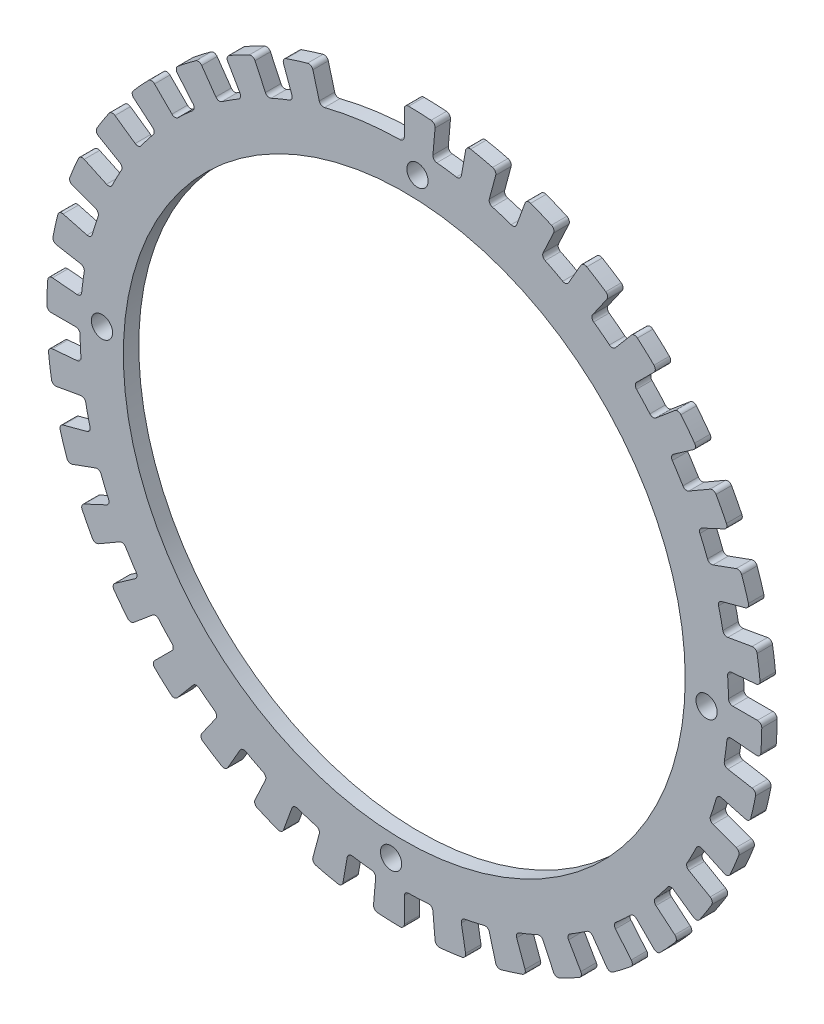
SolidWorks part; units mm, degrees
ref_plane "Front Plane" through (0, 0, 0) normal (0, 0, 1) x (1, 0, 0)
ref_plane "Top Plane" through (0, 0, 0) normal (0, 1, 0) x (1, 0, 0)
ref_plane "Right Plane" through (0, 0, 0) normal (1, 0, 0) x (0, 0, -1)
sketch "Sketch1" plane through (0, 0, 0) normal (0, 0, 1) x (1, 0, 0)
  line L0 (0, 82.7) -> (0, 75) construction
  line L1 (7.2078, 82.3853) -> (6.5367, 74.7146) construction
  line L2 (0, 75) -> (0, 0) construction
  line L3 (6.5367, 74.7146) -> (0, 0) construction
  line L4 (13.1961, 74.8389) -> (14.186, 80.4528) construction
  line L5 (13.1961, 74.8389) -> (0, 0) construction
  line L8 (0, 0) -> (3.0531, 69.9286) construction
  line L12 (3.2715, 74.9286) -> (3.0531, 69.9286) construction
  line L15 (3.0531, 69.9286) -> (2.8348, 64.9286) construction
  line L18 (7.6195, 75.6171) -> (6.6233, 75.7042) construction
  line L21 (7.6195, 75.6171) -> (7.5192, 74.6221) construction
  line L24 (13.1961, 74.8389) -> (12.2113, 75.0126) construction
  line L27 (12.2113, 75.0126) -> (12.0506, 74.0256) construction
  line L30 (1.0122, 82.6938) -> (1, 81.6939) construction
  line L33 (1, 81.6939) -> (0, 81.6939) construction
  line L36 (7.1201, 81.383) -> (6.1239, 81.4702) construction
  line L39 (6.1239, 81.4702) -> (6.1989, 82.4674) construction
  line L42 (7.1201, 81.383) -> (6.6233, 75.7042)
  line L45 (0, 81.6939) -> (0, 75.9934)
  line L48 (0, 75.9934) -> (-1, 75.9934) construction
  line L51 (-1, 75.9934) -> (-0.9868, 74.9935) construction
  line L54 (14.186, 80.4528) -> (13.1961, 74.8389)
  line L57 (21.1439, 78.9102) -> (19.6685, 73.404)
  line L59 (27.941, 76.7671) -> (25.9913, 71.4105)
  line L62 (34.5253, 74.0398) -> (32.1162, 68.8734)
  line L65 (40.8469, 70.749) -> (37.9967, 65.8122)
  line L68 (46.8577, 66.9197) -> (43.588, 62.2502)
  line L72 (52.5118, 62.5811) -> (48.8476, 58.2143)
  line L74 (57.7663, 57.7663) -> (53.7355, 53.7355)
  line L77 (62.5811, 52.5118) -> (58.2143, 48.8476)
  line L80 (66.9197, 46.8577) -> (62.2502, 43.588)
  line L83 (70.749, 40.8469) -> (65.8122, 37.9967)
  line L86 (74.0398, 34.5253) -> (68.8734, 32.1162)
  line L89 (76.7671, 27.941) -> (71.4105, 25.9913)
  line L92 (78.9102, 21.1439) -> (73.404, 19.6685)
  line L95 (80.4528, 14.186) -> (74.8389, 13.1961)
  line L98 (81.383, 7.1201) -> (75.7042, 6.6233)
  line L101 (81.6939, 0) -> (75.9934, 0)
  line L104 (81.383, -7.1201) -> (75.7042, -6.6233)
  line L107 (80.4528, -14.186) -> (74.8389, -13.1961)
  line L108 (78.9102, -21.1439) -> (73.404, -19.6685)
  line L109 (0, -82.7) -> (0, -75) [skipped]
  line L110 (76.7671, -27.941) -> (71.4105, -25.9913)
  line L111 (14.3607, 81.4436) -> (13.0236, 73.8606) [skipped]
  line L112 (74.0398, -34.5253) -> (68.8734, -32.1162)
  line L113 (70.749, -40.8469) -> (65.8122, -37.9967)
  line L114 (66.9197, -46.8577) -> (62.2502, -43.588)
  line L115 (41.35, 71.6203) -> (37.5, 64.9519) [skipped]
  line L116 (62.5811, -52.5118) -> (58.2143, -48.8476)
  line L117 (53.1585, 63.3519) -> (48.2091, 57.4533) [skipped]
  line L118 (-63.3519, -53.1585) -> (-57.4533, -48.2091) [skipped]
  line L119 (63.3519, 53.1585) -> (57.4533, 48.2091) [skipped]
  line L120 (57.7663, -57.7663) -> (53.7355, -53.7355)
  line L121 (71.6203, 41.35) -> (64.9519, 37.5) [skipped]
  line L122 (52.5118, -62.5811) -> (48.8476, -58.2143)
  line L123 (77.7126, 28.2851) -> (70.4769, 25.6515) [skipped]
  line L124 (46.8577, -66.9197) -> (43.588, -62.2502)
  line L125 (81.4436, 14.3607) -> (73.8606, 13.0236) [skipped]
  line L126 (40.8469, -70.749) -> (37.9967, -65.8122)
  line L127 (82.7, 0) -> (75, 0) [skipped]
  line L128 (34.5253, -74.0398) -> (32.1162, -68.8734)
  line L129 (81.4436, -14.3607) -> (73.8606, -13.0236) [skipped]
  line L130 (27.941, -76.7671) -> (25.9913, -71.4105)
  line L131 (77.7126, -28.2851) -> (70.4769, -25.6515) [skipped]
  line L132 (21.1439, -78.9102) -> (19.6685, -73.404)
  line L133 (71.6203, -41.35) -> (64.9519, -37.5) [skipped]
  line L134 (14.186, -80.4528) -> (13.1961, -74.8389)
  line L135 (63.3519, -53.1585) -> (57.4533, -48.2091) [skipped]
  line L136 (7.1201, -81.383) -> (6.6233, -75.7042)
  line L137 (53.1585, -63.3519) -> (48.2091, -57.4533) [skipped]
  line L138 (0, -81.6939) -> (0, -75.9934)
  line L139 (41.35, -71.6203) -> (37.5, -64.9519) [skipped]
  line L140 (-7.1201, -81.383) -> (-6.6233, -75.7042)
  line L141 (28.2851, -77.7126) -> (25.6515, -70.4769) [skipped]
  line L142 (14.3607, -81.4436) -> (13.0236, -73.8606) [skipped]
  line L143 (34.9505, 74.9517) -> (31.6964, 67.9731) [skipped]
  line L144 (47.4348, 67.7439) -> (43.0182, 61.4364) [skipped]
  line L145 (58.4777, 58.4777) -> (53.033, 53.033) [skipped]
  line L146 (67.7439, 47.4348) -> (61.4364, 43.0182) [skipped]
  line L147 (74.9517, 34.9505) -> (67.9731, 31.6964) [skipped]
  line L148 (79.8821, 21.4043) -> (72.4444, 19.4114) [skipped]
  line L149 (82.3853, 7.2078) -> (74.7146, 6.5367) [skipped]
  line L150 (82.3853, -7.2078) -> (74.7146, -6.5367) [skipped]
  line L151 (79.8821, -21.4043) -> (72.4444, -19.4114) [skipped]
  line L152 (74.9517, -34.9505) -> (67.9731, -31.6964) [skipped]
  line L153 (67.7439, -47.4348) -> (61.4364, -43.0182) [skipped]
  line L154 (58.4777, -58.4777) -> (53.033, -53.033) [skipped]
  line L155 (47.4348, -67.7439) -> (43.0182, -61.4364) [skipped]
  line L156 (34.9505, -74.9517) -> (31.6964, -67.9731) [skipped]
  line L157 (21.4043, -79.8821) -> (19.4114, -72.4444) [skipped]
  line L158 (7.2078, -82.3853) -> (6.5367, -74.7146) [skipped]
  line L159 (-7.2078, -82.3853) -> (-6.5367, -74.7146) [skipped]
  line L160 (-21.4043, -79.8821) -> (-19.4114, -72.4444) [skipped]
  line L161 (-34.9505, -74.9517) -> (-31.6964, -67.9731) [skipped]
  line L162 (-47.4348, -67.7439) -> (-43.0182, -61.4364) [skipped]
  line L163 (-58.4777, -58.4777) -> (-53.033, -53.033) [skipped]
  line L164 (-67.7439, -47.4348) -> (-61.4364, -43.0182) [skipped]
  line L165 (-74.9517, -34.9505) -> (-67.9731, -31.6964) [skipped]
  line L166 (-79.8821, -21.4043) -> (-72.4444, -19.4114) [skipped]
  line L167 (-82.3853, -7.2078) -> (-74.7146, -6.5367) [skipped]
  line L168 (-82.3853, 7.2078) -> (-74.7146, 6.5367) [skipped]
  line L169 (-79.8821, 21.4043) -> (-72.4444, 19.4114) [skipped]
  line L170 (-74.9517, 34.9505) -> (-67.9731, 31.6964) [skipped]
  line L171 (-67.7439, 47.4348) -> (-61.4364, 43.0182) [skipped]
  line L172 (-58.4777, 58.4777) -> (-53.033, 53.033) [skipped]
  line L173 (-47.4348, 67.7439) -> (-43.0182, 61.4364) [skipped]
  line L174 (-34.9505, 74.9517) -> (-31.6964, 67.9731) [skipped]
  line L175 (-21.4043, 79.8821) -> (-19.4114, 72.4444) [skipped]
  line L176 (21.4043, 79.8821) -> (19.4114, 72.4444) [skipped]
  line L177 (-14.186, -80.4528) -> (-13.1961, -74.8389)
  line L178 (-21.1439, -78.9102) -> (-19.6685, -73.404)
  line L179 (-27.941, -76.7671) -> (-25.9913, -71.4105)
  line L180 (-34.5253, -74.0398) -> (-32.1162, -68.8734)
  line L181 (-40.8469, -70.749) -> (-37.9967, -65.8122)
  line L182 (-46.8577, -66.9197) -> (-43.588, -62.2502)
  line L183 (-52.5118, -62.5811) -> (-48.8476, -58.2143)
  line L184 (-57.7663, -57.7663) -> (-53.7355, -53.7355)
  line L185 (-62.5811, -52.5118) -> (-58.2143, -48.8476)
  line L186 (-66.9197, -46.8577) -> (-62.2502, -43.588)
  line L187 (-70.749, -40.8469) -> (-65.8122, -37.9967)
  line L188 (-74.0398, -34.5253) -> (-68.8734, -32.1162)
  line L189 (-76.7671, -27.941) -> (-71.4105, -25.9913)
  line L190 (-78.9102, -21.1439) -> (-73.404, -19.6685)
  line L191 (-80.4528, -14.186) -> (-74.8389, -13.1961)
  line L192 (-81.383, -7.1201) -> (-75.7042, -6.6233)
  line L193 (-81.6939, 0) -> (-75.9934, 0)
  line L194 (-81.383, 7.1201) -> (-75.7042, 6.6233)
  line L195 (-80.4528, 14.186) -> (-74.8389, 13.1961)
  line L196 (-78.9102, 21.1439) -> (-73.404, 19.6685)
  line L197 (-76.7671, 27.941) -> (-71.4105, 25.9913)
  line L198 (-74.0398, 34.5253) -> (-68.8734, 32.1162)
  line L199 (-70.749, 40.8469) -> (-65.8122, 37.9967)
  line L200 (-66.9197, 46.8577) -> (-62.2502, 43.588)
  line L201 (-62.5811, 52.5118) -> (-58.2143, 48.8476)
  line L202 (-57.7663, 57.7663) -> (-53.7355, 53.7355)
  line L203 (-52.5118, 62.5811) -> (-48.8476, 58.2143)
  line L204 (-46.8577, 66.9197) -> (-43.588, 62.2502)
  line L205 (-40.8469, 70.749) -> (-37.9967, 65.8122)
  line L206 (-34.5253, 74.0398) -> (-32.1162, 68.8734)
  line L207 (-27.941, 76.7671) -> (-25.9913, 71.4105)
  line L208 (-21.1439, 78.9102) -> (-19.6685, 73.404)
  circle A0 centre (0, 0) radius 82.7 construction
  circle A1 centre (0, 0) radius 64.9905
  circle A73 centre (3.0531, 69.9286) radius 2.4585
  circle A74 centre (3.0531, 69.9286) radius 2.987 construction
  arc A78 (0, 75) -> (6.5367, 74.7146) centre (0, 0) cw construction
  arc A79 (6.6233, 75.7042) -> (7.5192, 74.6221) centre (7.6195, 75.6171) ccw
  arc A80 (12.0506, 74.0256) -> (13.1961, 74.8389) centre (12.2113, 75.0126) ccw construction
  arc A81 (7.1201, 81.383) -> (6.1989, 82.4674) centre (6.1239, 81.4702) ccw
  arc A82 (0, 81.6939) -> (1.0122, 82.6938) centre (1, 81.6939) cw
  arc A83 (6.5367, 74.7146) -> (13.0236, 73.8606) centre (0, 0) cw [skipped]
  arc A84 (7.5192, 74.6221) -> (12.0506, 74.0256) centre (0, 0) cw
  arc A85 (0, 82.7) -> (7.2078, 82.3853) centre (0, 0) cw [skipped]
  arc A86 (1.0122, 82.6938) -> (6.1989, 82.4674) centre (0, 0) cw
  arc A87 (28.2851, 77.7126) -> (34.9505, 74.9517) centre (0, 0) cw [skipped]
  arc A88 (31.6964, 67.9731) -> (37.5, 64.9519) centre (0, 0) cw [skipped]
  arc A89 (41.35, 71.6203) -> (47.4348, 67.7439) centre (0, 0) cw [skipped]
  arc A90 (43.0182, 61.4364) -> (48.2091, 57.4533) centre (0, 0) cw [skipped]
  arc A91 (53.1585, 63.3519) -> (58.4777, 58.4777) centre (0, 0) cw [skipped]
  arc A92 (53.033, 53.033) -> (57.4533, 48.2091) centre (0, 0) cw [skipped]
  arc A93 (63.3519, 53.1585) -> (67.7439, 47.4348) centre (0, 0) cw [skipped]
  arc A94 (61.4364, 43.0182) -> (64.9519, 37.5) centre (0, 0) cw [skipped]
  arc A95 (71.6203, 41.35) -> (74.9517, 34.9505) centre (0, 0) cw [skipped]
  arc A96 (67.9731, 31.6964) -> (70.4769, 25.6515) centre (0, 0) cw [skipped]
  arc A97 (77.7126, 28.2851) -> (79.8821, 21.4043) centre (0, 0) cw [skipped]
  arc A98 (72.4444, 19.4114) -> (73.8606, 13.0236) centre (0, 0) cw [skipped]
  arc A99 (81.4436, 14.3607) -> (82.3853, 7.2078) centre (0, 0) cw [skipped]
  arc A100 (74.7146, 6.5367) -> (75, 0) centre (0, 0) cw [skipped]
  arc A101 (82.7, 0) -> (82.3853, -7.2078) centre (0, 0) cw [skipped]
  arc A102 (74.7146, -6.5367) -> (73.8606, -13.0236) centre (0, 0) cw [skipped]
  arc A103 (81.4436, -14.3607) -> (79.8821, -21.4043) centre (0, 0) cw [skipped]
  arc A104 (72.4444, -19.4114) -> (70.4769, -25.6515) centre (0, 0) cw [skipped]
  arc A105 (77.7126, -28.2851) -> (74.9517, -34.9505) centre (0, 0) cw [skipped]
  arc A106 (67.9731, -31.6964) -> (64.9519, -37.5) centre (0, 0) cw [skipped]
  arc A107 (71.6203, -41.35) -> (67.7439, -47.4348) centre (0, 0) cw [skipped]
  arc A108 (61.4364, -43.0182) -> (57.4533, -48.2091) centre (0, 0) cw [skipped]
  arc A109 (63.3519, -53.1585) -> (58.4777, -58.4777) centre (0, 0) cw [skipped]
  arc A110 (53.033, -53.033) -> (48.2091, -57.4533) centre (0, 0) cw [skipped]
  arc A111 (53.1585, -63.3519) -> (47.4348, -67.7439) centre (0, 0) cw [skipped]
  arc A112 (43.0182, -61.4364) -> (37.5, -64.9519) centre (0, 0) cw [skipped]
  arc A113 (41.35, -71.6203) -> (34.9505, -74.9517) centre (0, 0) cw [skipped]
  arc A114 (31.6964, -67.9731) -> (25.6515, -70.4769) centre (0, 0) cw [skipped]
  arc A115 (28.2851, -77.7126) -> (21.4043, -79.8821) centre (0, 0) cw [skipped]
  arc A116 (19.4114, -72.4444) -> (13.0236, -73.8606) centre (0, 0) cw [skipped]
  arc A117 (14.3607, -81.4436) -> (7.2078, -82.3853) centre (0, 0) cw [skipped]
  arc A118 (6.5367, -74.7146) -> (0, -75) centre (0, 0) cw [skipped]
  arc A119 (0, -82.7) -> (-7.2078, -82.3853) centre (0, 0) cw [skipped]
  arc A120 (-6.5367, -74.7146) -> (-13.0236, -73.8606) centre (0, 0) cw [skipped]
  arc A121 (-14.3607, -81.4436) -> (-21.4043, -79.8821) centre (0, 0) cw [skipped]
  arc A122 (-28.2851, -77.7126) -> (-34.9505, -74.9517) centre (0, 0) cw [skipped]
  arc A123 (-19.4114, -72.4444) -> (-25.6515, -70.4769) centre (0, 0) cw [skipped]
  arc A124 (-31.6964, -67.9731) -> (-37.5, -64.9519) centre (0, 0) cw [skipped]
  arc A125 (-41.35, -71.6203) -> (-47.4348, -67.7439) centre (0, 0) cw [skipped]
  arc A126 (-43.0182, -61.4364) -> (-48.2091, -57.4533) centre (0, 0) cw [skipped]
  arc A127 (-53.1585, -63.3519) -> (-58.4777, -58.4777) centre (0, 0) cw [skipped]
  arc A128 (-53.033, -53.033) -> (-57.4533, -48.2091) centre (0, 0) cw [skipped]
  arc A129 (-63.3519, -53.1585) -> (-67.7439, -47.4348) centre (0, 0) cw [skipped]
  arc A130 (-61.4364, -43.0182) -> (-64.9519, -37.5) centre (0, 0) cw [skipped]
  arc A131 (-71.6203, -41.35) -> (-74.9517, -34.9505) centre (0, 0) cw [skipped]
  arc A132 (-67.9731, -31.6964) -> (-70.4769, -25.6515) centre (0, 0) cw [skipped]
  arc A133 (-77.7126, -28.2851) -> (-79.8821, -21.4043) centre (0, 0) cw [skipped]
  arc A134 (-72.4444, -19.4114) -> (-73.8606, -13.0236) centre (0, 0) cw [skipped]
  arc A135 (-81.4436, -14.3607) -> (-82.3853, -7.2078) centre (0, 0) cw [skipped]
  arc A136 (-74.7146, -6.5367) -> (-75, 0) centre (0, 0) cw [skipped]
  arc A137 (-82.7, 0) -> (-82.3853, 7.2078) centre (0, 0) cw [skipped]
  arc A138 (-74.7146, 6.5367) -> (-73.8606, 13.0236) centre (0, 0) cw [skipped]
  arc A139 (-81.4436, 14.3607) -> (-79.8821, 21.4043) centre (0, 0) cw [skipped]
  arc A140 (-72.4444, 19.4114) -> (-70.4769, 25.6515) centre (0, 0) cw [skipped]
  arc A141 (-77.7126, 28.2851) -> (-74.9517, 34.9505) centre (0, 0) cw [skipped]
  arc A142 (-67.9731, 31.6964) -> (-64.9519, 37.5) centre (0, 0) cw [skipped]
  arc A143 (-71.6203, 41.35) -> (-67.7439, 47.4348) centre (0, 0) cw [skipped]
  arc A144 (-61.4364, 43.0182) -> (-57.4533, 48.2091) centre (0, 0) cw [skipped]
  arc A145 (-63.3519, 53.1585) -> (-58.4777, 58.4777) centre (0, 0) cw [skipped]
  arc A146 (-53.033, 53.033) -> (-48.2091, 57.4533) centre (0, 0) cw [skipped]
  arc A147 (-53.1585, 63.3519) -> (-47.4348, 67.7439) centre (0, 0) cw [skipped]
  arc A148 (-43.0182, 61.4364) -> (-37.5, 64.9519) centre (0, 0) cw [skipped]
  arc A149 (-41.35, 71.6203) -> (-34.9505, 74.9517) centre (0, 0) cw [skipped]
  arc A150 (-31.6964, 67.9731) -> (-25.6515, 70.4769) centre (0, 0) cw [skipped]
  arc A151 (-28.2851, 77.7126) -> (-21.4043, 79.8821) centre (0, 0) cw [skipped]
  arc A152 (-19.4114, 72.4444) -> (-13.0236, 73.8606) centre (0, 0) cw [skipped]
  arc A153 (14.3607, 81.4436) -> (21.4043, 79.8821) centre (0, 0) cw [skipped]
  arc A154 (19.4114, 72.4444) -> (25.6515, 70.4769) centre (0, 0) cw [skipped]
  arc A155 (0, 75.9934) -> (-0.9868, 74.9935) centre (-1, 75.9934) cw
  arc A156 (13.1961, 74.8389) -> (12.0506, 74.0256) centre (12.2113, 75.0126) cw
  arc A157 (14.186, 80.4528) -> (15.3565, 81.2617) centre (15.1708, 80.2791) cw
  arc A158 (15.3565, 81.2617) -> (20.425, 80.1381) centre (0, 0) cw
  arc A159 (21.1439, 78.9102) -> (20.425, 80.1381) centre (20.178, 79.169) ccw
  arc A160 (19.6685, 73.404) -> (20.363, 72.1828) centre (20.6345, 73.1452) ccw
  arc A161 (20.363, 72.1828) -> (24.722, 70.8084) centre (0, 0) cw
  arc A162 (25.9913, 71.4105) -> (24.722, 70.8084) centre (25.0516, 71.7525) cw
  arc A163 (27.941, 76.7671) -> (29.2341, 77.3606) centre (28.8806, 76.4251) cw
  arc A164 (29.2341, 77.3606) -> (34.0305, 75.3738) centre (0, 0) cw
  arc A165 (34.5253, 74.0398) -> (34.0305, 75.3738) centre (33.619, 74.4624) ccw
  arc A166 (32.1162, 68.8734) -> (32.588, 67.5501) centre (33.0225, 68.4508) ccw
  arc A167 (32.588, 67.5501) -> (36.6421, 65.4397) centre (0, 0) cw
  arc A168 (37.9967, 65.8122) -> (36.6421, 65.4397) centre (37.1307, 66.3122) cw
  arc A169 (40.8469, 70.749) -> (42.2235, 71.1088) centre (41.713, 70.249) cw
  arc A170 (42.2235, 71.1088) -> (46.602, 68.3194) centre (0, 0) cw
  arc A171 (46.8577, 66.9197) -> (46.602, 68.3194) centre (46.0385, 67.4933) ccw
  arc A172 (43.588, 62.2502) -> (43.8229, 60.8651) centre (44.4072, 61.6766) ccw
  arc A173 (43.8229, 60.8651) -> (47.4489, 58.0827) centre (0, 0) cw
  arc A174 (48.8476, 58.2143) -> (47.4489, 58.0827) centre (48.0816, 58.8571) cw
  arc A175 (52.5118, 62.5811) -> (53.93, 62.6965) centre (53.2779, 61.9384) cw
  arc A176 (53.93, 62.6965) -> (57.7576, 59.1891) centre (0, 0) cw
  arc A177 (57.7663, 57.7663) -> (57.7576, 59.1891) centre (57.0592, 58.4734) ccw
  arc A178 (53.7355, 53.7355) -> (53.7262, 52.3306) centre (54.4426, 53.0284) ccw
  arc A179 (53.7262, 52.3306) -> (56.814, 48.9609) centre (0, 0) cw
  arc A180 (58.2143, 48.8476) -> (56.814, 48.9609) centre (57.5716, 49.6137) cw
  arc A181 (62.5811, 52.5118) -> (63.9978, 52.3791) centre (63.2239, 51.7458) cw
  arc A182 (63.9978, 52.3791) -> (67.1582, 48.2604) centre (0, 0) cw
  arc A183 (66.9197, 46.8577) -> (67.1582, 48.2604) centre (66.3461, 47.6768) ccw
  arc A184 (62.2502, 43.588) -> (61.9971, 42.2061) centre (62.8237, 42.7689) ccw
  arc A185 (61.9971, 42.2061) -> (64.4529, 38.3514) centre (0, 0) cw
  arc A186 (65.8122, 37.9967) -> (64.4529, 38.3514) centre (65.3122, 38.8627) cw
  arc A187 (70.749, 40.8469) -> (72.1211, 40.4703) centre (71.249, 39.9809) cw
  arc A188 (72.1211, 40.4703) -> (74.5182, 35.8653) centre (0, 0) cw
  arc A189 (74.0398, 34.5253) -> (74.5182, 35.8653) centre (73.6172, 35.4316) ccw
  arc A190 (68.8734, 32.1162) -> (68.3843, 30.7992) centre (69.296, 31.2099) ccw
  arc A191 (68.3843, 30.7992) -> (70.1333, 26.5766) centre (0, 0) cw
  arc A192 (71.4105, 25.9913) -> (70.1333, 26.5766) centre (71.0684, 26.931) cw
  arc A193 (76.7671, 27.941) -> (78.053, 27.3318) centre (77.1092, 27.0013) cw
  arc A194 (78.053, 27.3318) -> (79.6141, 22.3805) centre (0, 0) cw
  arc A195 (78.9102, 21.1439) -> (79.6141, 22.3805) centre (78.6514, 22.1099) ccw
  arc A196 (73.404, 19.6685) -> (72.6936, 18.4565) centre (73.6628, 18.7026) ccw
  arc A197 (72.6936, 18.4565) -> (73.6828, 13.9943) centre (0, 0) cw
  arc A198 (74.8389, 13.1961) -> (73.6828, 13.9943) centre (74.6653, 14.1809) cw
  arc A199 (80.4528, 14.186) -> (81.6133, 13.3628) centre (80.6264, 13.2012) cw
  arc A200 (81.6133, 13.3628) -> (82.2909, 8.2156) centre (0, 0) cw
  arc A201 (81.383, 7.1201) -> (82.2909, 8.2156) centre (81.2959, 8.1163) ccw
  arc A202 (75.7042, 6.6233) -> (74.7941, 5.553) centre (75.7914, 5.6271) ccw
  arc A203 (74.7941, 5.553) -> (74.9935, 0.9868) centre (0, 0) cw
  arc A204 (75.9934, 0) -> (74.9935, 0.9868) centre (75.9934, 1) cw
  arc A205 (81.6939, 0) -> (82.6938, -1.0122) centre (81.6939, -1) cw
  arc A206 (82.6938, -1.0122) -> (82.4674, -6.1989) centre (0, 0) cw
  arc A207 (81.383, -7.1201) -> (82.4674, -6.1989) centre (81.4702, -6.1239) ccw
  arc A208 (75.7042, -6.6233) -> (74.6221, -7.5192) centre (75.6171, -7.6195) ccw
  arc A209 (74.6221, -7.5192) -> (74.0256, -12.0506) centre (0, 0) cw
  arc A210 (74.8389, -13.1961) -> (74.0256, -12.0506) centre (75.0126, -12.2113) cw
  arc A211 (80.4528, -14.186) -> (81.2617, -15.3565) centre (80.2791, -15.1708) cw
  arc A212 (81.2617, -15.3565) -> (80.1381, -20.425) centre (0, 0) cw
  arc A213 (78.9102, -21.1439) -> (80.1381, -20.425) centre (79.169, -20.178) ccw
  arc A214 (73.404, -19.6685) -> (72.1828, -20.363) centre (73.1452, -20.6345) ccw
  arc A215 (72.1828, -20.363) -> (70.8084, -24.722) centre (0, 0) cw
  arc A216 (71.4105, -25.9913) -> (70.8084, -24.722) centre (71.7525, -25.0516) cw
  arc A217 (76.7671, -27.941) -> (77.3606, -29.2341) centre (76.4251, -28.8806) cw
  arc A218 (77.3606, -29.2341) -> (75.3738, -34.0305) centre (0, 0) cw
  arc A219 (74.0398, -34.5253) -> (75.3738, -34.0305) centre (74.4624, -33.619) ccw
  arc A220 (68.8734, -32.1162) -> (67.5501, -32.588) centre (68.4508, -33.0225) ccw
  arc A221 (67.5501, -32.588) -> (65.4397, -36.6421) centre (0, 0) cw
  arc A222 (65.8122, -37.9967) -> (65.4397, -36.6421) centre (66.3122, -37.1307) cw
  arc A223 (70.749, -40.8469) -> (71.1088, -42.2235) centre (70.249, -41.713) cw
  arc A224 (71.1088, -42.2235) -> (68.3194, -46.602) centre (0, 0) cw
  arc A225 (66.9197, -46.8577) -> (68.3194, -46.602) centre (67.4933, -46.0385) ccw
  arc A226 (62.2502, -43.588) -> (60.8651, -43.8229) centre (61.6766, -44.4072) ccw
  arc A227 (60.8651, -43.8229) -> (58.0827, -47.4489) centre (0, 0) cw
  arc A228 (58.2143, -48.8476) -> (58.0827, -47.4489) centre (58.8571, -48.0816) cw
  arc A229 (62.5811, -52.5118) -> (62.6965, -53.93) centre (61.9384, -53.2779) cw
  arc A230 (62.6965, -53.93) -> (59.1891, -57.7576) centre (0, 0) cw
  arc A231 (57.7663, -57.7663) -> (59.1891, -57.7576) centre (58.4734, -57.0592) ccw
  arc A232 (53.7355, -53.7355) -> (52.3306, -53.7262) centre (53.0284, -54.4426) ccw
  arc A233 (52.3306, -53.7262) -> (48.9609, -56.814) centre (0, 0) cw
  arc A234 (48.8476, -58.2143) -> (48.9609, -56.814) centre (49.6137, -57.5716) cw
  arc A235 (52.5118, -62.5811) -> (52.3791, -63.9978) centre (51.7458, -63.2239) cw
  arc A236 (52.3791, -63.9978) -> (48.2604, -67.1582) centre (0, 0) cw
  arc A237 (46.8577, -66.9197) -> (48.2604, -67.1582) centre (47.6768, -66.3461) ccw
  arc A238 (43.588, -62.2502) -> (42.2061, -61.9971) centre (42.7689, -62.8237) ccw
  arc A239 (42.2061, -61.9971) -> (38.3514, -64.4529) centre (0, 0) cw
  arc A240 (37.9967, -65.8122) -> (38.3514, -64.4529) centre (38.8627, -65.3122) cw
  arc A241 (40.8469, -70.749) -> (40.4703, -72.1211) centre (39.9809, -71.249) cw
  arc A242 (40.4703, -72.1211) -> (35.8653, -74.5182) centre (0, 0) cw
  arc A243 (34.5253, -74.0398) -> (35.8653, -74.5182) centre (35.4316, -73.6172) ccw
  arc A244 (32.1162, -68.8734) -> (30.7992, -68.3843) centre (31.2099, -69.296) ccw
  arc A245 (30.7992, -68.3843) -> (26.5766, -70.1333) centre (0, 0) cw
  arc A246 (25.9913, -71.4105) -> (26.5766, -70.1333) centre (26.931, -71.0684) cw
  arc A247 (27.941, -76.7671) -> (27.3318, -78.053) centre (27.0013, -77.1092) cw
  arc A248 (27.3318, -78.053) -> (22.3805, -79.6141) centre (0, 0) cw
  arc A249 (21.1439, -78.9102) -> (22.3805, -79.6141) centre (22.1099, -78.6514) ccw
  arc A250 (19.6685, -73.404) -> (18.4565, -72.6936) centre (18.7026, -73.6628) ccw
  arc A251 (18.4565, -72.6936) -> (13.9943, -73.6828) centre (0, 0) cw
  arc A252 (13.1961, -74.8389) -> (13.9943, -73.6828) centre (14.1809, -74.6653) cw
  arc A253 (14.186, -80.4528) -> (13.3628, -81.6133) centre (13.2012, -80.6264) cw
  arc A254 (13.3628, -81.6133) -> (8.2156, -82.2909) centre (0, 0) cw
  arc A255 (7.1201, -81.383) -> (8.2156, -82.2909) centre (8.1163, -81.2959) ccw
  arc A256 (6.6233, -75.7042) -> (5.553, -74.7941) centre (5.6271, -75.7914) ccw
  arc A257 (5.553, -74.7941) -> (0.9868, -74.9935) centre (0, 0) cw
  arc A258 (0, -75.9934) -> (0.9868, -74.9935) centre (1, -75.9934) cw
  arc A259 (0, -81.6939) -> (-1.0122, -82.6938) centre (-1, -81.6939) cw
  arc A260 (-1.0122, -82.6938) -> (-6.1989, -82.4674) centre (0, 0) cw
  arc A261 (-7.1201, -81.383) -> (-6.1989, -82.4674) centre (-6.1239, -81.4702) ccw
  arc A262 (-6.6233, -75.7042) -> (-7.5192, -74.6221) centre (-7.6195, -75.6171) ccw
  arc A263 (-7.5192, -74.6221) -> (-12.0506, -74.0256) centre (0, 0) cw
  arc A264 (-13.1961, -74.8389) -> (-12.0506, -74.0256) centre (-12.2113, -75.0126) cw
  arc A265 (-14.186, -80.4528) -> (-15.3565, -81.2617) centre (-15.1708, -80.2791) cw
  arc A266 (-15.3565, -81.2617) -> (-20.425, -80.1381) centre (0, 0) cw
  arc A267 (-21.1439, -78.9102) -> (-20.425, -80.1381) centre (-20.178, -79.169) ccw
  arc A268 (-19.6685, -73.404) -> (-20.363, -72.1828) centre (-20.6345, -73.1452) ccw
  arc A269 (-20.363, -72.1828) -> (-24.722, -70.8084) centre (0, 0) cw
  arc A270 (-25.9913, -71.4105) -> (-24.722, -70.8084) centre (-25.0516, -71.7525) cw
  arc A271 (-27.941, -76.7671) -> (-29.2341, -77.3606) centre (-28.8806, -76.4251) cw
  arc A272 (-29.2341, -77.3606) -> (-34.0305, -75.3738) centre (0, 0) cw
  arc A273 (-34.5253, -74.0398) -> (-34.0305, -75.3738) centre (-33.619, -74.4624) ccw
  arc A274 (-32.1162, -68.8734) -> (-32.588, -67.5501) centre (-33.0225, -68.4508) ccw
  arc A275 (-32.588, -67.5501) -> (-36.6421, -65.4397) centre (0, 0) cw
  arc A276 (-37.9967, -65.8122) -> (-36.6421, -65.4397) centre (-37.1307, -66.3122) cw
  arc A277 (-40.8469, -70.749) -> (-42.2235, -71.1088) centre (-41.713, -70.249) cw
  arc A278 (-42.2235, -71.1088) -> (-46.602, -68.3194) centre (0, 0) cw
  arc A279 (-46.8577, -66.9197) -> (-46.602, -68.3194) centre (-46.0385, -67.4933) ccw
  arc A280 (-43.588, -62.2502) -> (-43.8229, -60.8651) centre (-44.4072, -61.6766) ccw
  arc A281 (-43.8229, -60.8651) -> (-47.4489, -58.0827) centre (0, 0) cw
  arc A282 (-48.8476, -58.2143) -> (-47.4489, -58.0827) centre (-48.0816, -58.8571) cw
  arc A283 (-52.5118, -62.5811) -> (-53.93, -62.6965) centre (-53.2779, -61.9384) cw
  arc A284 (-53.93, -62.6965) -> (-57.7576, -59.1891) centre (0, 0) cw
  arc A285 (-57.7663, -57.7663) -> (-57.7576, -59.1891) centre (-57.0592, -58.4734) ccw
  arc A286 (-53.7355, -53.7355) -> (-53.7262, -52.3306) centre (-54.4426, -53.0284) ccw
  arc A287 (-53.7262, -52.3306) -> (-56.814, -48.9609) centre (0, 0) cw
  arc A288 (-58.2143, -48.8476) -> (-56.814, -48.9609) centre (-57.5716, -49.6137) cw
  arc A289 (-62.5811, -52.5118) -> (-63.9978, -52.3791) centre (-63.2239, -51.7458) cw
  arc A290 (-63.9978, -52.3791) -> (-67.1582, -48.2604) centre (0, 0) cw
  arc A291 (-66.9197, -46.8577) -> (-67.1582, -48.2604) centre (-66.3461, -47.6768) ccw
  arc A292 (-62.2502, -43.588) -> (-61.9971, -42.2061) centre (-62.8237, -42.7689) ccw
  arc A293 (-61.9971, -42.2061) -> (-64.4529, -38.3514) centre (0, 0) cw
  arc A294 (-65.8122, -37.9967) -> (-64.4529, -38.3514) centre (-65.3122, -38.8627) cw
  arc A295 (-70.749, -40.8469) -> (-72.1211, -40.4703) centre (-71.249, -39.9809) cw
  arc A296 (-72.1211, -40.4703) -> (-74.5182, -35.8653) centre (0, 0) cw
  arc A297 (-74.0398, -34.5253) -> (-74.5182, -35.8653) centre (-73.6172, -35.4316) ccw
  arc A298 (-68.8734, -32.1162) -> (-68.3843, -30.7992) centre (-69.296, -31.2099) ccw
  arc A299 (-68.3843, -30.7992) -> (-70.1333, -26.5766) centre (0, 0) cw
  arc A300 (-71.4105, -25.9913) -> (-70.1333, -26.5766) centre (-71.0684, -26.931) cw
  arc A301 (-76.7671, -27.941) -> (-78.053, -27.3318) centre (-77.1092, -27.0013) cw
  arc A302 (-78.053, -27.3318) -> (-79.6141, -22.3805) centre (0, 0) cw
  arc A303 (-78.9102, -21.1439) -> (-79.6141, -22.3805) centre (-78.6514, -22.1099) ccw
  arc A304 (-73.404, -19.6685) -> (-72.6936, -18.4565) centre (-73.6628, -18.7026) ccw
  arc A305 (-72.6936, -18.4565) -> (-73.6828, -13.9943) centre (0, 0) cw
  arc A306 (-74.8389, -13.1961) -> (-73.6828, -13.9943) centre (-74.6653, -14.1809) cw
  arc A307 (-80.4528, -14.186) -> (-81.6133, -13.3628) centre (-80.6264, -13.2012) cw
  arc A308 (-81.6133, -13.3628) -> (-82.2909, -8.2156) centre (0, 0) cw
  arc A309 (-81.383, -7.1201) -> (-82.2909, -8.2156) centre (-81.2959, -8.1163) ccw
  arc A310 (-75.7042, -6.6233) -> (-74.7941, -5.553) centre (-75.7914, -5.6271) ccw
  arc A311 (-74.7941, -5.553) -> (-74.9935, -0.9868) centre (0, 0) cw
  arc A312 (-75.9934, 0) -> (-74.9935, -0.9868) centre (-75.9934, -1) cw
  arc A313 (-81.6939, 0) -> (-82.6938, 1.0122) centre (-81.6939, 1) cw
  arc A314 (-82.6938, 1.0122) -> (-82.4674, 6.1989) centre (0, 0) cw
  arc A315 (-81.383, 7.1201) -> (-82.4674, 6.1989) centre (-81.4702, 6.1239) ccw
  arc A316 (-75.7042, 6.6233) -> (-74.6221, 7.5192) centre (-75.6171, 7.6195) ccw
  arc A317 (-74.6221, 7.5192) -> (-74.0256, 12.0506) centre (0, 0) cw
  arc A318 (-74.8389, 13.1961) -> (-74.0256, 12.0506) centre (-75.0126, 12.2113) cw
  arc A319 (-80.4528, 14.186) -> (-81.2617, 15.3565) centre (-80.2791, 15.1708) cw
  arc A320 (-81.2617, 15.3565) -> (-80.1381, 20.425) centre (0, 0) cw
  arc A321 (-78.9102, 21.1439) -> (-80.1381, 20.425) centre (-79.169, 20.178) ccw
  arc A322 (-73.404, 19.6685) -> (-72.1828, 20.363) centre (-73.1452, 20.6345) ccw
  arc A323 (-72.1828, 20.363) -> (-70.8084, 24.722) centre (0, 0) cw
  arc A324 (-71.4105, 25.9913) -> (-70.8084, 24.722) centre (-71.7525, 25.0516) cw
  arc A325 (-76.7671, 27.941) -> (-77.3606, 29.2341) centre (-76.4251, 28.8806) cw
  arc A326 (-77.3606, 29.2341) -> (-75.3738, 34.0305) centre (0, 0) cw
  arc A327 (-74.0398, 34.5253) -> (-75.3738, 34.0305) centre (-74.4624, 33.619) ccw
  arc A328 (-68.8734, 32.1162) -> (-67.5501, 32.588) centre (-68.4508, 33.0225) ccw
  arc A329 (-67.5501, 32.588) -> (-65.4397, 36.6421) centre (0, 0) cw
  arc A330 (-65.8122, 37.9967) -> (-65.4397, 36.6421) centre (-66.3122, 37.1307) cw
  arc A331 (-70.749, 40.8469) -> (-71.1088, 42.2235) centre (-70.249, 41.713) cw
  arc A332 (-71.1088, 42.2235) -> (-68.3194, 46.602) centre (0, 0) cw
  arc A333 (-66.9197, 46.8577) -> (-68.3194, 46.602) centre (-67.4933, 46.0385) ccw
  arc A334 (-62.2502, 43.588) -> (-60.8651, 43.8229) centre (-61.6766, 44.4072) ccw
  arc A335 (-60.8651, 43.8229) -> (-58.0827, 47.4489) centre (0, 0) cw
  arc A336 (-58.2143, 48.8476) -> (-58.0827, 47.4489) centre (-58.8571, 48.0816) cw
  arc A337 (-62.5811, 52.5118) -> (-62.6965, 53.93) centre (-61.9384, 53.2779) cw
  arc A338 (-62.6965, 53.93) -> (-59.1891, 57.7576) centre (0, 0) cw
  arc A339 (-57.7663, 57.7663) -> (-59.1891, 57.7576) centre (-58.4734, 57.0592) ccw
  arc A340 (-53.7355, 53.7355) -> (-52.3306, 53.7262) centre (-53.0284, 54.4426) ccw
  arc A341 (-52.3306, 53.7262) -> (-48.9609, 56.814) centre (0, 0) cw
  arc A342 (-48.8476, 58.2143) -> (-48.9609, 56.814) centre (-49.6137, 57.5716) cw
  arc A343 (-52.5118, 62.5811) -> (-52.3791, 63.9978) centre (-51.7458, 63.2239) cw
  arc A344 (-52.3791, 63.9978) -> (-48.2604, 67.1582) centre (0, 0) cw
  arc A345 (-46.8577, 66.9197) -> (-48.2604, 67.1582) centre (-47.6768, 66.3461) ccw
  arc A346 (-43.588, 62.2502) -> (-42.2061, 61.9971) centre (-42.7689, 62.8237) ccw
  arc A347 (-42.2061, 61.9971) -> (-38.3514, 64.4529) centre (0, 0) cw
  arc A348 (-37.9967, 65.8122) -> (-38.3514, 64.4529) centre (-38.8627, 65.3122) cw
  arc A349 (-40.8469, 70.749) -> (-40.4703, 72.1211) centre (-39.9809, 71.249) cw
  arc A350 (-40.4703, 72.1211) -> (-35.8653, 74.5182) centre (0, 0) cw
  arc A351 (-34.5253, 74.0398) -> (-35.8653, 74.5182) centre (-35.4316, 73.6172) ccw
  arc A352 (-32.1162, 68.8734) -> (-30.7992, 68.3843) centre (-31.2099, 69.296) ccw
  arc A353 (-30.7992, 68.3843) -> (-26.5766, 70.1333) centre (0, 0) cw
  arc A354 (-25.9913, 71.4105) -> (-26.5766, 70.1333) centre (-26.931, 71.0684) cw
  arc A355 (-27.941, 76.7671) -> (-27.3318, 78.053) centre (-27.0013, 77.1092) cw
  arc A356 (-27.3318, 78.053) -> (-22.3805, 79.6141) centre (0, 0) cw
  arc A357 (-21.1439, 78.9102) -> (-22.3805, 79.6141) centre (-22.1099, 78.6514) ccw
  arc A358 (-19.6685, 73.404) -> (-18.4565, 72.6936) centre (-18.7026, 73.6628) ccw
  arc A359 (-18.4565, 72.6936) -> (-13.9943, 73.6828) centre (0, 0) cw
  arc A360 (-13.9943, 73.6828) -> (-0.9868, 74.9935) centre (0, 0) cw
  circle A361 centre (69.9286, -3.0531) radius 2.4585
  circle A362 centre (-3.0531, -69.9286) radius 2.4585
  circle A363 centre (-69.9286, 3.0531) radius 2.4585
  point P29 (0, 0)
  point P34 (0.515, 2.7252)
  point P252 (0, 0)
  point P763 (0, 0)
  dimension "D1" = 5
  dimension "D2" = 165.4
  dimension "D7" = 4.917
  dimension "D8" = 5.974
  dimension "D12" = 1
  dimension "D3" = 5
  dimension "D4" = 7.7
  dimension "D6" = 2.5
  dimension "D10" = 69.9952
  dimension "D11" = 5
  dimension "D5" = 35
  dimension "D13" = 35
extrude "Boss-Extrude1" add sketch "Sketch1" along normal blind 3.5719
